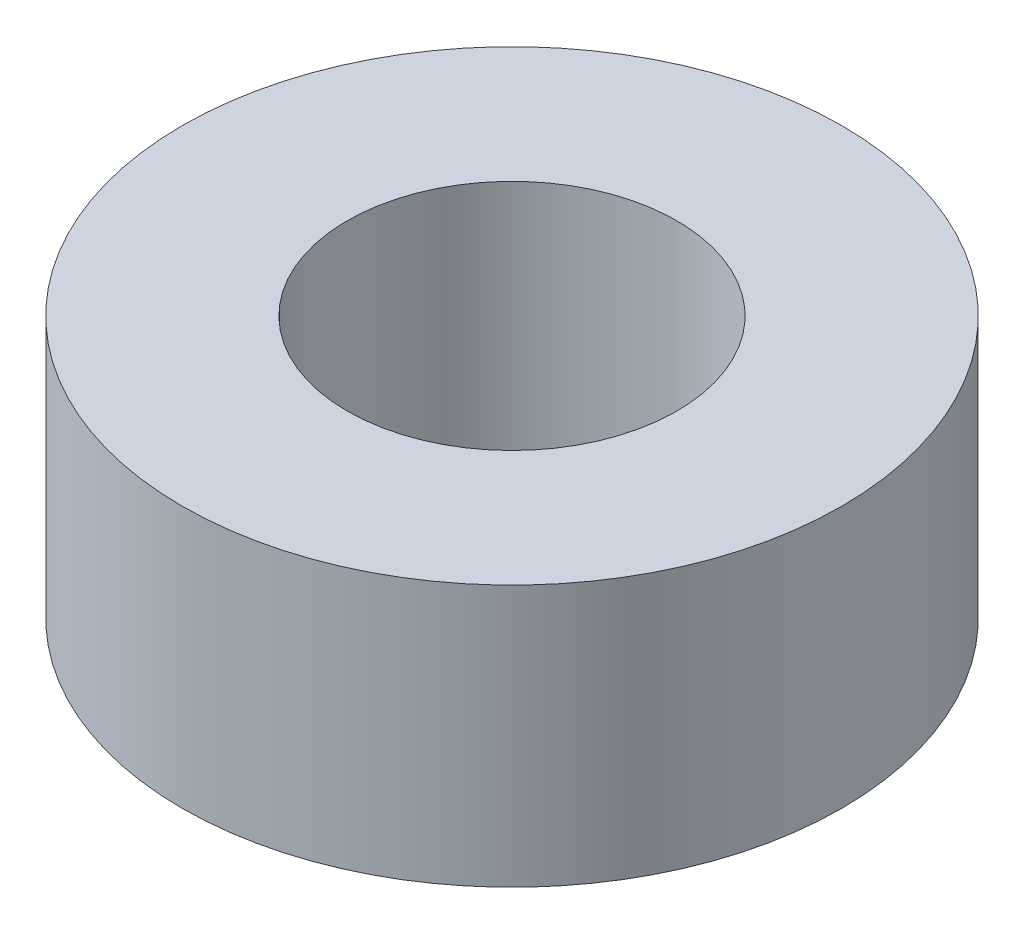
SolidWorks part; units mm, degrees
ref_plane "Front Plane" through (0, 0, 0) normal (0, 0, 1) x (1, 0, 0)
ref_plane "Top Plane" through (0, 0, 0) normal (0, 1, 0) x (1, 0, 0)
ref_plane "Right Plane" through (0, 0, 0) normal (1, 0, 0) x (0, 0, -1)
sketch "Sketch1" plane through (0, 0, 0) normal (0, 1, 0) x (1, 0, 0)
  circle A0 centre (0, 0) radius 4
  circle A1 centre (0, 0) radius 8
  dimension "D1" = 8
  dimension "D2" = 16
extrude "Boss-Extrude1" add sketch "Sketch1" along normal mid plane 6.35
